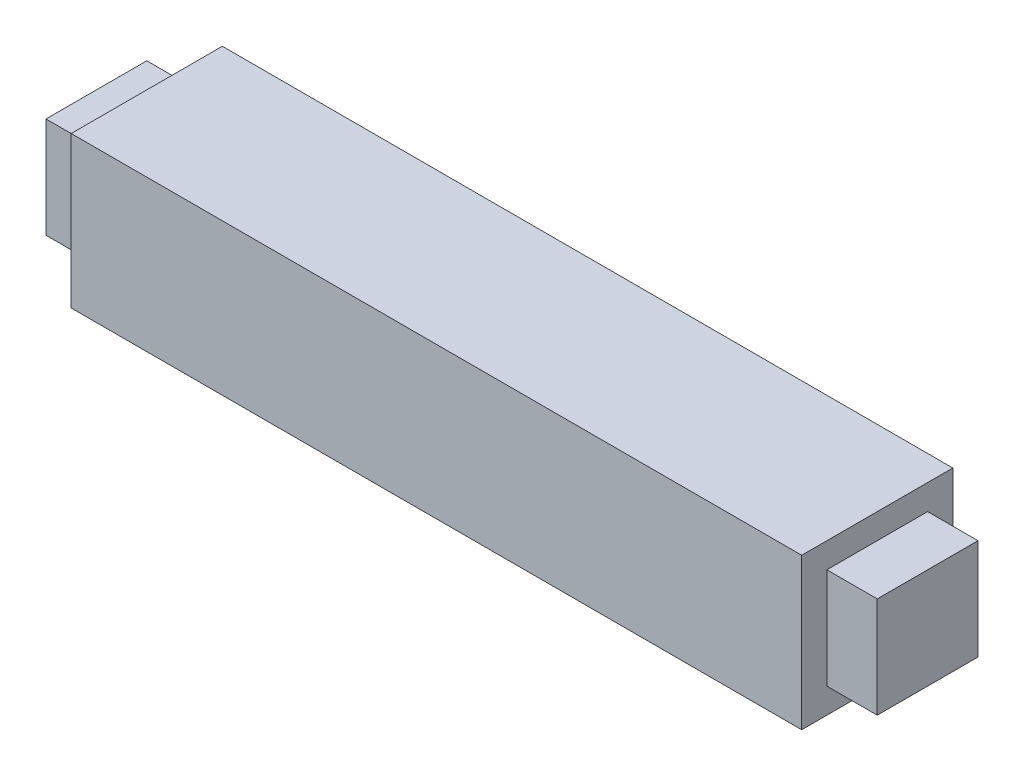
SolidWorks part; units mm, degrees
ref_plane "Front Plane" through (0, 0, 0) normal (0, 0, 1) x (1, 0, 0)
ref_plane "Top Plane" through (0, 0, 0) normal (0, 1, 0) x (1, 0, 0)
ref_plane "Right Plane" through (0, 0, 0) normal (1, 0, 0) x (0, 0, -1)
sketch "Sketch1" plane through (0, 0, 0) normal (0, 0, 1) x (1, 0, 0)
  line L1 (-72.5, -15) -> (72.5, -15)
  line L2 (-72.5, -15) -> (-72.5, 15)
  line L3 (-72.5, 15) -> (72.5, 15)
  line L4 (72.5, -15) -> (72.5, 15)
extrude "Boss-Extrude1" add sketch "Sketch1" along normal mid plane 30
sketch "Sketch2" plane through (72.5, 0, 0) normal (1, 0, 0) x (0, 0, -1)
  line L1 (-10, -10) -> (10, -10)
  line L2 (-10, -10) -> (-10, 10)
  line L3 (-10, 10) -> (10, 10)
  line L4 (10, -10) -> (10, 10)
extrude "Boss-Extrude2" add sketch "Sketch2" along normal blind 10
sketch "Sketch3" plane through (-72.5, 0, 0) normal (-1, 0, 0) x (0, 0, 1)
  line L1 (-10, -10) -> (10, -10)
  line L2 (-10, -10) -> (-10, 10)
  line L3 (-10, 10) -> (10, 10)
  line L4 (10, -10) -> (10, 10)
extrude "Boss-Extrude3" add sketch "Sketch3" along normal blind 10
